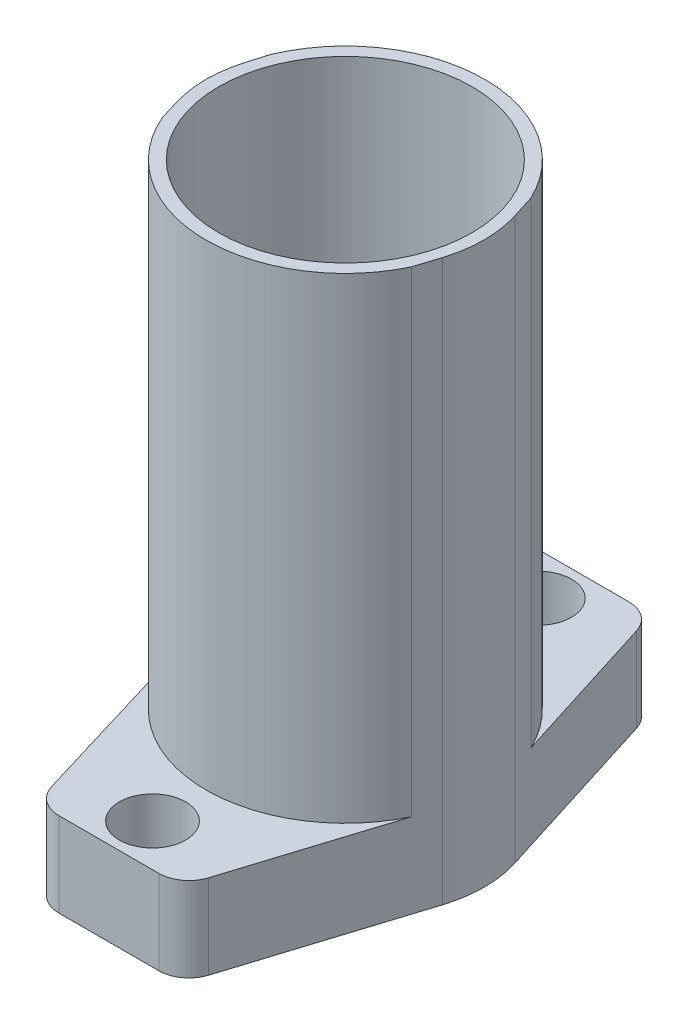
SolidWorks part; units mm, degrees
ref_plane "前视基准面" through (0, 0, 0) normal (0, 0, 1) x (1, 0, 0)
ref_plane "上视基准面" through (0, 0, 0) normal (0, 1, 0) x (1, 0, 0)
ref_plane "右视基准面" through (0, 0, 0) normal (1, 0, 0) x (0, 0, -1)
sketch "草图1" plane through (0, 0, 0) normal (0, 1, 0) x (1, 0, 0)
  line L0 (-46.1114, 0) -> (46.1114, 0) construction
  line L1 (0, 0) -> (0, 16) construction
  line L2 (-6.1122, 19.5) -> (5.8592, 19.5)
  line L3 (-6.1122, 19.5) -> (-11.1273, 2.8905)
  line L4 (5.8592, 19.5) -> (11.0541, 3.0037)
  line L5 (5.8592, -19.5) -> (11.0541, -3.0037)
  line L6 (-6.1122, -19.5) -> (-11.1273, -2.8905)
  line L7 (-6.1122, -19.5) -> (5.8592, -19.5)
  circle A0 centre (0, 16) radius 2.75
  circle A1 centre (0, 0) radius 10.25 construction
  circle A2 centre (0, 0) radius 3.25
  circle A3 centre (0, -16) radius 2.75
  arc A4 (11.0541, 3.0037) -> (11.0541, -3.0037) centre (1.5159, 0) cw
  arc A5 (-11.1273, 2.8905) -> (-11.1273, -2.8905) centre (-1.5541, 0) ccw
  point P4 (0, 0)
  point P11 (-0.1265, 19.5)
  point P20 (12, 0)
  point P23 (-12, 0)
  dimension "D2" = 5.5
  dimension "D3" = 20.5
  dimension "D6" = 3.5
  dimension "D7" = 6.5
  dimension "D8" = 10
  dimension "D1" = 16
  dimension "D4" = 12
  dimension "D5" = 12
extrude "凸台-拉伸1" add sketch "草图1" along normal blind 46.5
sketch "草图2" plane through (0, 46.5, 0) normal (0, 1, 0) x (1, 0, 0)
  line L0 (5.8592, -19.5) -> (11.0541, -3.0037) construction
  line L1 (-6.1122, -19.5) -> (5.8592, -19.5) construction
  line L2 (-11.1273, -2.8905) -> (-6.1122, -19.5) construction
  line L3 (-6.1122, 19.5) -> (-11.1273, 2.8905) construction
  line L4 (5.8592, 19.5) -> (-6.1122, 19.5) construction
  line L5 (11.0541, 3.0037) -> (5.8592, 19.5) construction
  line L6 (5.8592, -19.5) -> (11.0541, -3.0037)
  line L7 (-6.1122, -19.5) -> (5.8592, -19.5)
  line L8 (-11.1273, -2.8905) -> (-6.1122, -19.5)
  line L9 (-6.1122, 19.5) -> (-11.1273, 2.8905)
  line L10 (5.8592, 19.5) -> (-6.1122, 19.5)
  line L11 (11.0541, 3.0037) -> (5.8592, 19.5)
  circle A0 centre (0, 0) radius 10.5
  circle A1 centre (0, 0) radius 11.5541
  circle A2 centre (0, 16) radius 2.75 construction
  circle A3 centre (0, 16) radius 2.75
  circle M2 centre (0, 16) radius 2.75
  line M4 (5.8592, 19.5) -> (-6.1122, 19.5)
  line M5 (-6.1122, 19.5) -> (-11.1273, 2.8905)
  line M7 (-6.1122, -19.5) -> (5.8592, -19.5)
  line M8 (5.8592, -19.5) -> (11.0541, -3.0037)
  circle M9 centre (0, 0) radius 3.25
  circle M10 centre (0, -16) radius 2.75
  dimension "D1" = 21
extrude "切除-拉伸1" cut sketch "草图2" against normal blind 21.5 contours A0 M9 | A1 L11 M4 M5 M2 | A1 L8 M7 M8 M10
sketch "草图4" plane through (0, 0, 0) normal (0, -1, 0) x (1, 0, 0)
  circle A0 centre (0, 0) radius 5
  dimension "D1" = 10
extrude "切除-拉伸3" cut sketch "草图4" against normal blind 15
sketch "草图5" plane through (0, 25, 0) normal (0, 1, 0) x (1, 0, 0)
  line L3 (10.4434, 4.943) -> (5.8592, 19.5)
  line L4 (5.8592, 19.5) -> (-6.1122, 19.5)
  line L5 (-6.1122, 19.5) -> (-10.64, 4.5041)
  line L6 (10.4434, 4.943) -> (5.8592, 19.5)
  line L7 (5.8592, 19.5) -> (-6.1122, 19.5)
  line L8 (-6.1122, 19.5) -> (-10.64, 4.5041)
  line L9 (-10.64, -4.5041) -> (-6.1122, -19.5)
  line L10 (-6.1122, -19.5) -> (5.8592, -19.5)
  line L11 (5.8592, -19.5) -> (10.4434, -4.943)
  line L12 (-10.64, -4.5041) -> (-6.1122, -19.5)
  line L13 (-6.1122, -19.5) -> (5.8592, -19.5)
  line L14 (5.8592, -19.5) -> (10.4434, -4.943)
  arc A1 (10.4434, 4.943) -> (-10.64, 4.5041) centre (0, 0) ccw
  arc A2 (10.4434, 4.943) -> (-10.64, 4.5041) centre (0, 0) ccw
  arc A3 (-10.64, -4.5041) -> (10.4434, -4.943) centre (0, 0) ccw
  arc A4 (-10.64, -4.5041) -> (10.4434, -4.943) centre (0, 0) ccw
  dimension "D1" = 0
  dimension "D2" = 0
extrude "切除-拉伸4" cut sketch "草图5" against normal offset from surface (13 mm away) 12 up to face at (0, 0, -5)
fillet "圆角1" radius 2.5 4 edges at (-6.1122, 6, 19.5) (5.8592, 6, 19.5) (5.8592, 6, -19.5) (-6.1122, 6, -19.5)
sketch "草图6" plane through (0, 12, 0) normal (0, 1, 0) x (1, 0, 0)
  line L3 (10.4434, 4.943) -> (6.41, 17.7509)
  line L4 (4.0254, 19.5) -> (-4.2556, 19.5)
  line L5 (-6.6489, 17.7226) -> (-10.64, 4.5041)
  line L6 (10.4434, 4.943) -> (6.41, 17.7509)
  line L7 (4.0254, 19.5) -> (-4.2556, 19.5)
  line L8 (-6.6489, 17.7226) -> (-10.64, 4.5041)
  line L9 (-10.64, -4.5041) -> (-6.6489, -17.7226)
  line L10 (-4.2556, -19.5) -> (4.0254, -19.5)
  line L11 (6.41, -17.7509) -> (10.4434, -4.943)
  line L12 (-10.64, -4.5041) -> (-6.6489, -17.7226)
  line L13 (-4.2556, -19.5) -> (4.0254, -19.5)
  line L14 (6.41, -17.7509) -> (10.4434, -4.943)
  arc A3 (6.41, 17.7509) -> (4.0254, 19.5) centre (4.0254, 17) ccw
  arc A4 (-4.2556, 19.5) -> (-6.6489, 17.7226) centre (-4.2556, 17) ccw
  arc A5 (10.4434, 4.943) -> (-10.64, 4.5041) centre (0, 0) ccw
  arc A6 (6.41, 17.7509) -> (4.0254, 19.5) centre (4.0254, 17) ccw
  arc A7 (-4.2556, 19.5) -> (-6.6489, 17.7226) centre (-4.2556, 17) ccw
  arc A8 (10.4434, 4.943) -> (-10.64, 4.5041) centre (0, 0) ccw
  arc A9 (-6.6489, -17.7226) -> (-4.2556, -19.5) centre (-4.2556, -17) ccw
  arc A10 (4.0254, -19.5) -> (6.41, -17.7509) centre (4.0254, -17) ccw
  arc A11 (-10.64, -4.5041) -> (10.4434, -4.943) centre (0, 0) ccw
  arc A12 (-6.6489, -17.7226) -> (-4.2556, -19.5) centre (-4.2556, -17) ccw
  arc A13 (4.0254, -19.5) -> (6.41, -17.7509) centre (4.0254, -17) ccw
  arc A14 (-10.64, -4.5041) -> (10.4434, -4.943) centre (0, 0) ccw
  dimension "D1" = 0
  dimension "D2" = 0
extrude "切除-拉伸5" cut sketch "草图6" against normal offset from surface (5 mm away) 7 up to face at (0, 0, -5)
